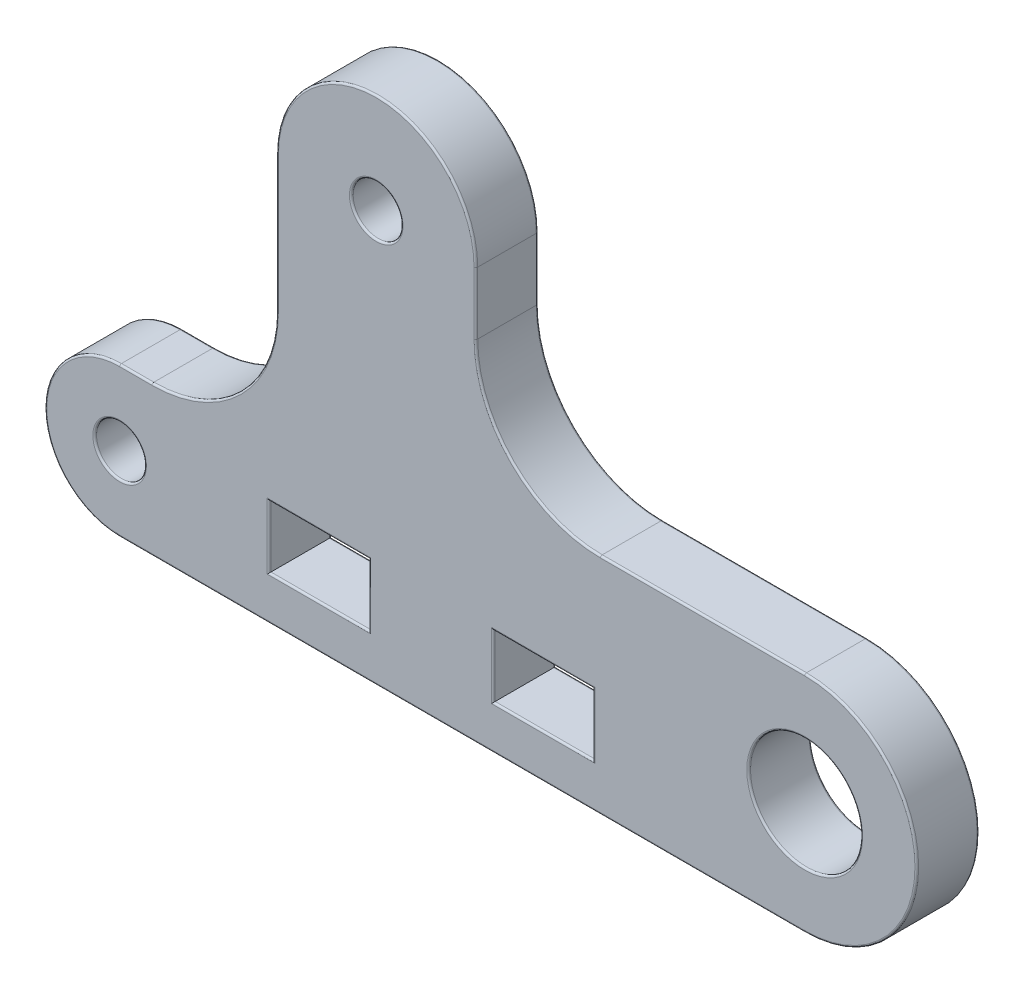
SolidWorks part; units mm, degrees
ref_plane "Front Plane" through (0, 0, 0) normal (0, 0, 1) x (1, 0, 0)
ref_plane "Top Plane" through (0, 0, 0) normal (0, 1, 0) x (1, 0, 0)
ref_plane "Right Plane" through (0, 0, 0) normal (1, 0, 0) x (0, 0, -1)
sketch "Sketch1" plane through (0, 0, 0) normal (0, 0, 1) x (1, 0, 0)
  line L0 (-27.5, 0) -> (27.5, 0)
  line L1 (1.1, 33) -> (1.1, 28)
  line L2 (11.1, 18) -> (27.5, 18)
  line L3 (-27.5, 12) -> (-24.9, 12)
  line L4 (-14.9, 22) -> (-14.9, 33)
  line L5 (-27.5, 6) -> (-15.5, 6) construction
  line L7 (-15.5, 8.5) -> (-7.5, 8.5)
  line L8 (-15.5, 8.5) -> (-15.5, 3.5)
  line L9 (-15.5, 3.5) -> (-7.5, 3.5)
  line L10 (-7.5, 8.5) -> (-7.5, 3.5)
  line L11 (2.5, 3.5) -> (10.5, 3.5)
  line L12 (2.5, 3.5) -> (2.5, 8.5)
  line L13 (2.5, 8.5) -> (10.5, 8.5)
  line L14 (10.5, 3.5) -> (10.5, 8.5)
  arc A0 (27.5, 0) -> (27.5, 18) centre (27.5, 9) ccw
  arc A1 (-27.5, 0) -> (-27.5, 12) centre (-27.5, 6) cw
  circle A2 centre (27.5, 9) radius 4.5
  circle A3 centre (-27.5, 6) radius 2
  circle A4 centre (-6.9, 33) radius 2
  circle A5 centre (-6.9, 33) radius 8 construction
  arc A6 (-14.9, 33) -> (1.1, 33) centre (-6.9, 33) cw
  arc A7 (1.1, 28) -> (11.1, 18) centre (11.1, 28) ccw
  arc A8 (-24.9, 12) -> (-14.9, 22) centre (-24.9, 22) ccw
  point P3 (0, 0)
  dimension "D2" = 9
  dimension "D3" = 6
  dimension "D4" = 9
  dimension "D5" = 4
  dimension "D6" = 33
  dimension "D8" = 16
  dimension "D9" = 10
  dimension "D1" = 55
  dimension "D7" = 6.9
  dimension "D10" = 12
  dimension "D11" = 8
  dimension "D12" = 5
  dimension "D13" = 10
extrude "Boss-Extrude1" add sketch "Sketch1" along normal mid plane 5
fillet "Fillet1" radius 0.15 42 edges at (10.5, 6, -2.5) (6.5, 3.5, -2.5) (2.5, 6, -2.5) (6.5, 8.5, -2.5) (-4.9, 33, -2.5) (32, 9, -2.5) (0, 0, -2.5) (36.5, 9, -2.5) (19.3, 18, -2.5) (4.0289, 20.9289, -2.5) (1.1, 30.5, -2.5) (-6.9, 41, -2.5) (-14.9, 27.5, -2.5) (-17.8289, 14.9289, -2.5) (-26.2, 12, -2.5) (-33.5, 6, -2.5) (-25.5, 6, -2.5) (-7.5, 6, -2.5) (-11.5, 3.5, -2.5) (-15.5, 6, -2.5) (-11.5, 8.5, -2.5) (6.5, 3.5, 2.5) (10.5, 6, 2.5) (6.5, 8.5, 2.5) (2.5, 6, 2.5) (-4.9, 33, 2.5) (32, 9, 2.5) (-26.2, 12, 2.5) (-17.8289, 14.9289, 2.5) (-14.9, 27.5, 2.5) (-6.9, 41, 2.5) (1.1, 30.5, 2.5) (4.0289, 20.9289, 2.5) (19.3, 18, 2.5) (36.5, 9, 2.5) (0, 0, 2.5) (-33.5, 6, 2.5) (-25.5, 6, 2.5) (-11.5, 3.5, 2.5) (-7.5, 6, 2.5) (-11.5, 8.5, 2.5) (-15.5, 6, 2.5)
